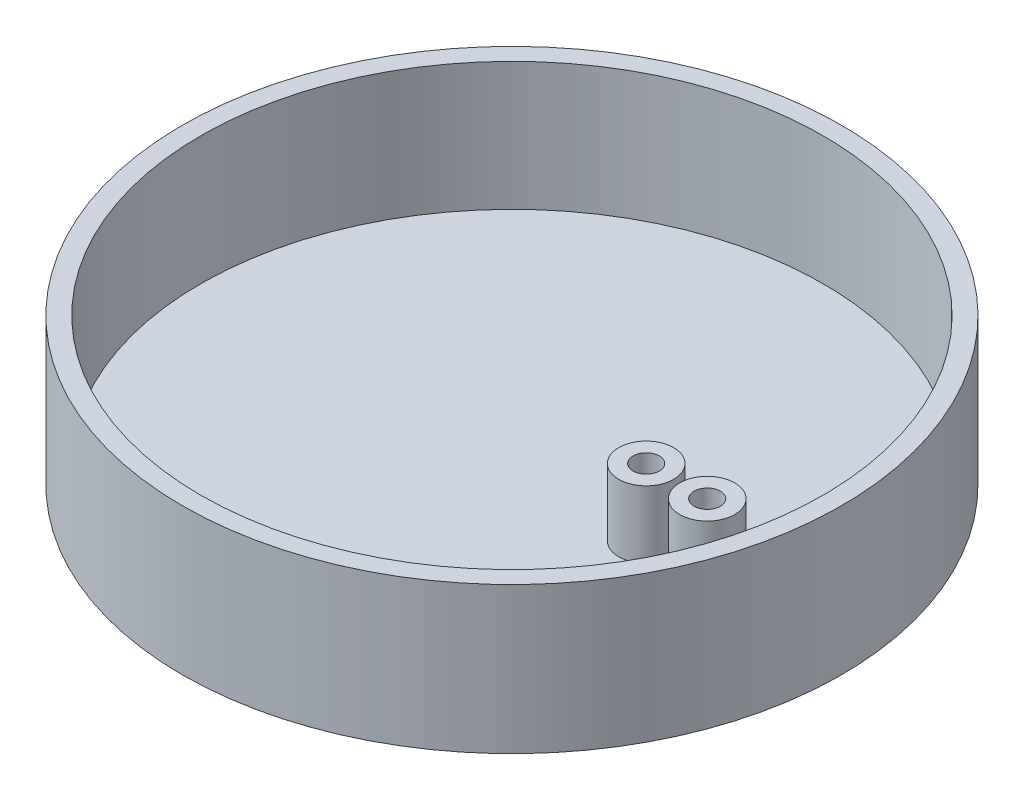
SolidWorks part; units mm, degrees
ref_plane "前视基准面" through (0, 0, 0) normal (0, 0, 1) x (1, 0, 0)
ref_plane "上视基准面" through (0, 0, 0) normal (0, 1, 0) x (1, 0, 0)
ref_plane "右视基准面" through (0, 0, 0) normal (1, 0, 0) x (0, 0, -1)
other "Configuration Table"
sketch "草图1" plane through (0, 0, 0) normal (0, 1, 0) x (1, 0, 0)
  circle A0 centre (0, 0) radius 54
extrude "Floor_D108_T3" add sketch "草图1" along normal blind 3
sketch "草图2" plane through (0, 0, 0) normal (0, 1, 0) x (1, 0, 0)
  circle A0 centre (0, 0) radius 54
  circle A1 centre (0, 0) radius 51
extrude "Rim_OD108_ID102_H24" add sketch "草图2" along normal blind 24
sketch "草图3" plane through (0, 0, 0) normal (0, 1, 0) x (1, 0, 0)
  circle A0 centre (22, 0) radius 4.5
  circle A1 centre (32, 0) radius 4.5
extrude "Sensor_fixed_posts" add sketch "草图3" along normal blind 14
sketch "草图4" plane through (0, 0, 0) normal (0, 1, 0) x (1, 0, 0)
  circle A0 centre (22, 0) radius 2.15
  circle A1 centre (32, 0) radius 2.15
extrude "M4_fixed_mount_clearance" cut sketch "草图4" along normal blind 14
